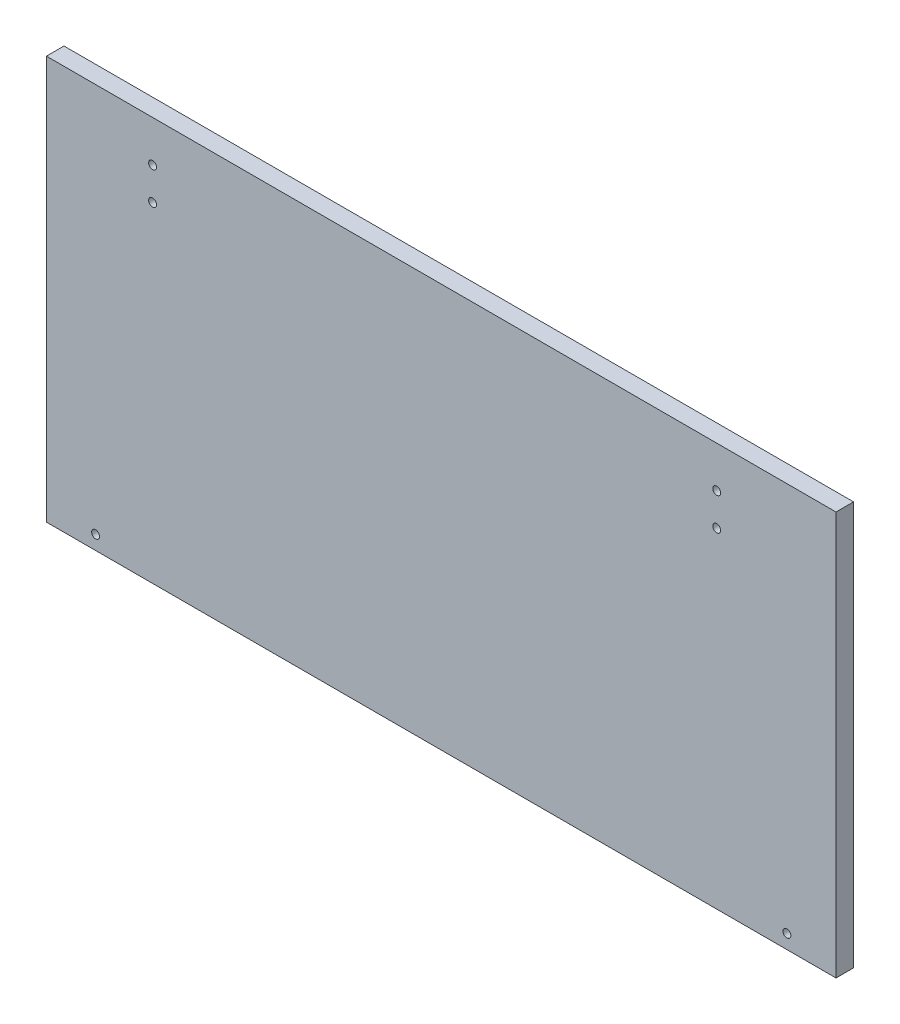
SolidWorks part; units mm, degrees
material "Multistrato di pioppo"
ref_plane "Piano frontale" through (0, 0, 0) normal (0, 0, 1) x (1, 0, 0)
ref_plane "Piano superiore" through (0, 0, 0) normal (0, 1, 0) x (1, 0, 0)
ref_plane "Piano destro" through (0, 0, 0) normal (1, 0, 0) x (0, 0, -1)
sketch "Schizzo1" plane through (0, 0, 0) normal (0, 0, 1) x (1, 0, 0)
  line L5 (-225, 115) -> (225, 115)
  line L6 (-225, 115) -> (-225, -115)
  line L7 (-225, -115) -> (225, -115)
  line L8 (225, 115) -> (225, -115)
  line L9 (-225, 115) -> (225, -115) construction
  line L10 (-225, -115) -> (225, 115) construction
  point P8 (0, 0)
  dimension "D1" = 230
  dimension "D2" = 450
extrude "Estrusione-Estrusione1" add sketch "Schizzo1" along normal blind 10
sketch "Schizzo2" plane through (0, 0, 10) normal (0, 0, 1) x (1, 0, 0)
  circle A0 centre (-164.5, 91.5) radius 2.25
  circle A1 centre (-164.5, 73) radius 2.25
  circle A2 centre (157, 91.5) radius 2.25
  circle A3 centre (157, 73) radius 2.25
  dimension "D1" = 4.5
extrude "Taglio-Estrusione1" cut sketch "Schizzo2" against normal blind 10
sketch "Schizzo3" plane through (0, 0, 10) normal (0, 0, 1) x (1, 0, 0)
  line L0 (-225, 115) -> (-225, -115) construction
  line L1 (-225, -115) -> (225, -115) construction
  line L2 (-197, -107) -> (197, -107) construction
  line L3 (225, -115) -> (225, 115) construction
  circle A0 centre (-197, -107) radius 2.25
  circle A1 centre (197, -107) radius 2.25
  dimension "D1" = 4.5
  dimension "D4" = 28
  dimension "D2" = 28
  dimension "D3" = 8
extrude "Taglio-Estrusione2" cut sketch "Schizzo3" against normal blind 10
